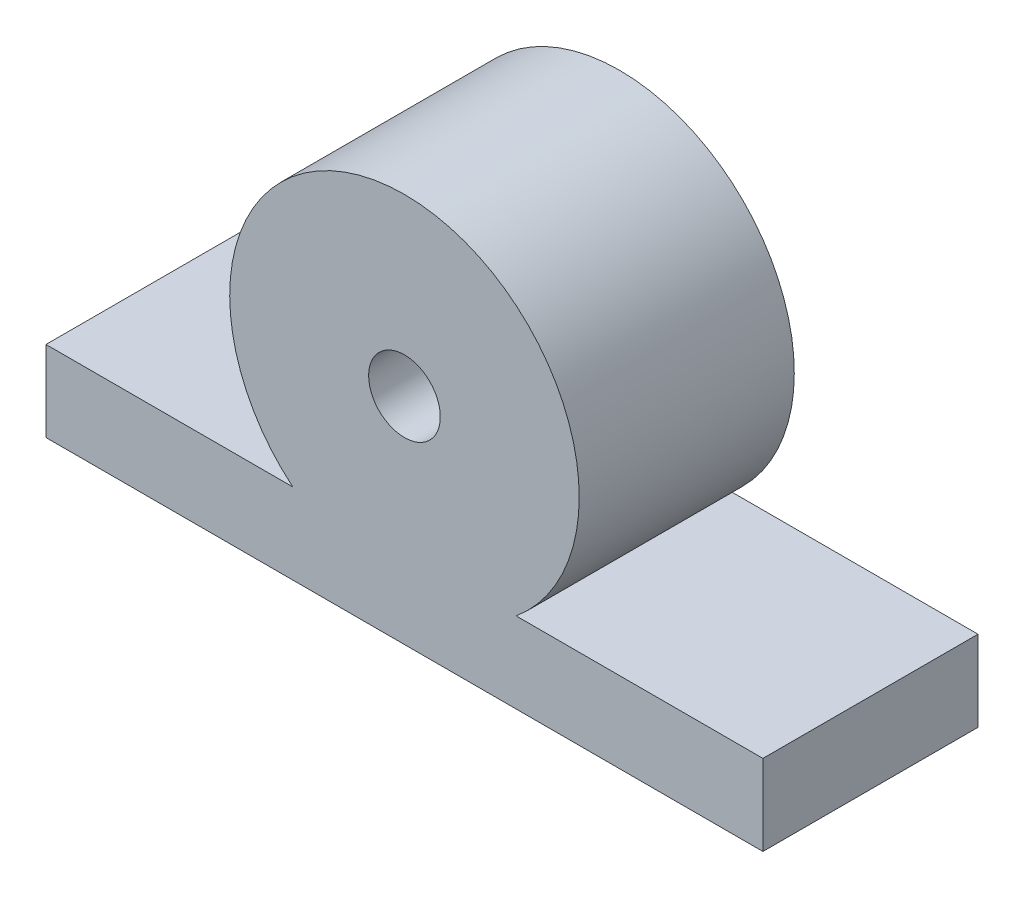
SolidWorks part; units mm, degrees
ref_plane "Front Plane" through (0, 0, 0) normal (0, 0, 1) x (1, 0, 0)
ref_plane "Top Plane" through (0, 0, 0) normal (0, 1, 0) x (1, 0, 0)
ref_plane "Right Plane" through (0, 0, 0) normal (1, 0, 0) x (0, 0, -1)
sketch "Sketch1" plane through (0, 0, 0) normal (0, 0, 1) x (1, 0, 0)
  line L0 (0, 0) -> (0, 7.1437) construction
  line L1 (-63.5, 0) -> (63.5, 0)
  line L2 (-63.5, 0) -> (-63.5, 14.2875)
  line L3 (-63.5, 14.2875) -> (-19.7801, 14.2875)
  line L4 (63.5, 14.2875) -> (63.5, 0)
  line L5 (19.7801, 14.2875) -> (63.5, 14.2875)
  line L6 (0, 14.2875) -> (0, 38.1) construction
  circle A0 centre (0, 38.1) radius 30.9562
  circle A1 centre (0, 38.1) radius 6.35
  point P6 (0, 0)
  dimension "D1" = 61.9125
  dimension "D3" = 12.7
  dimension "D2" = 38.1
  dimension "D4" = 14.2875
  dimension "D5" = 127
extrude "Boss-Extrude1" add sketch "Sketch1" along normal blind 38.1 contours A0 A1 | A0 L3 L2 L1 L4 L5
